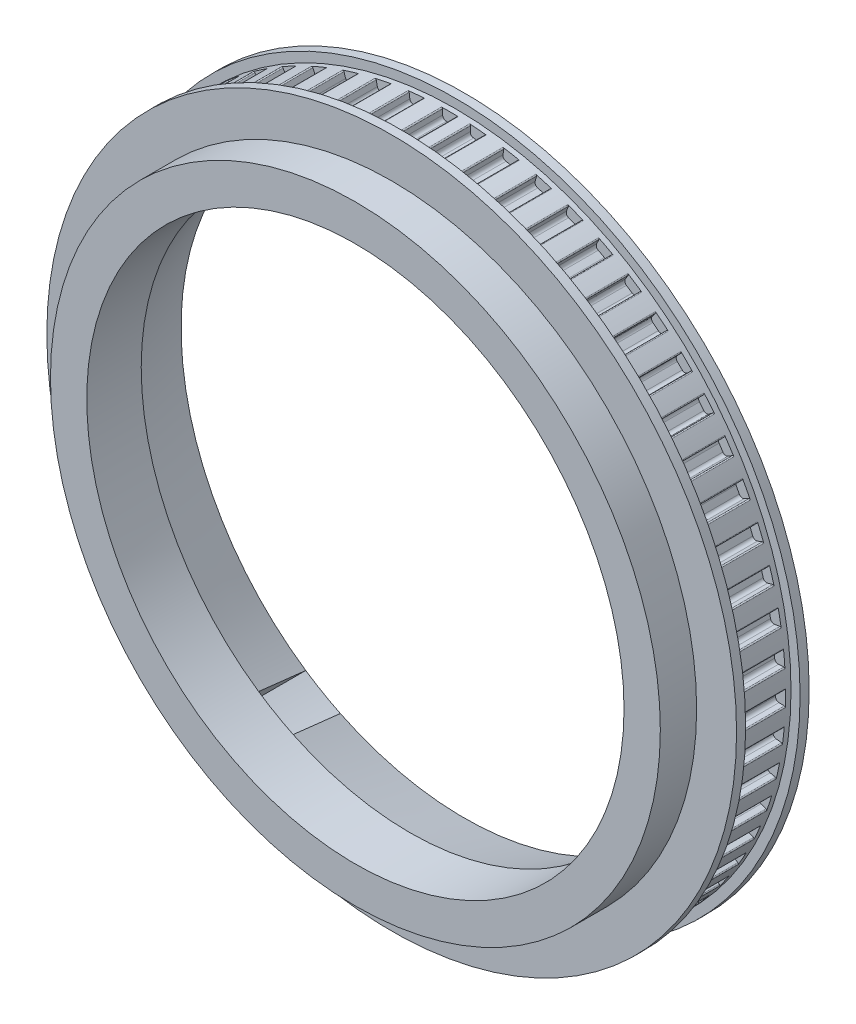
SolidWorks part; units mm, degrees
material "ABS"
ref_plane "Front Plane" through (0, 0, 0) normal (0, 0, 1) x (1, 0, 0)
ref_plane "Top Plane" through (0, 0, 0) normal (0, 1, 0) x (1, 0, 0)
ref_plane "Right Plane" through (0, 0, 0) normal (1, 0, 0) x (0, 0, -1)
sketch "Sketch2" plane through (0, 0, 0) normal (0, 1, 0) x (1, 0, 0)
  line L0 (0, -10) -> (0, 5) construction
  line L1 (37, -2.5) -> (37, -10)
  line L2 (37, -10) -> (42, -10)
  line L3 (42, -10) -> (42, -5)
  line L4 (42, -5) -> (47.5, -5)
  line L5 (47.5, -5) -> (47.5, -3.75)
  line L6 (47.5, 5) -> (39.0096, 5)
  line L7 (37, -2.5) -> (39.0096, 5)
  line L8 (47.5, 3.75) -> (46.25, 3.75)
  line L9 (46.25, 3.75) -> (46.25, -3.75)
  line L10 (46.25, -3.75) -> (47.5, -3.75)
  line L11 (47.5, 3.75) -> (47.5, 5)
  point P12 (-0.446, 0)
  point P15 (-2.0986, -0.9185)
  point P16 (0, 0)
  point P17 (46.25, 0)
  dimension "D1" = 15
  dimension "D2" = 5
  dimension "D3" = 5
  dimension "D4" = 15
  dimension "D5" = 7.5
  dimension "D6" = 47.5
  dimension "D7" = 42
  dimension "D8" = 1.25
  dimension "D9" = 7.5
revolve "Revolve1" add sketch "Sketch2" angle 360 about L0
sketch "Sketch4" plane through (0, 0, 0) normal (0, 0, -1) x (-1, 0, 0)
  line L0 (-0.9999, 46.2392) -> (-0.9701, 44.8595)
  line L1 (0.9701, 44.8595) -> (0.9999, 46.2392)
  circle A0 centre (0, 0) radius 46.25 construction
  arc A1 (-0.9999, 46.2392) -> (0.9999, 46.2392) centre (0, 0) cw
  arc A2 (-0.9701, 44.8595) -> (0.9701, 44.8595) centre (0, 0) cw
  point P8 (0, 44.87)
  point P9 (0, 46.25)
  dimension "D2" = 2
  dimension "D1" = 1.38
extrude "Cut-Extrude1" cut sketch "Sketch4" against normal mid plane 6
fillet "Fillet1" radius 0.15 2 edges at (0.9999, 46.2392, 0) (-0.9999, 46.2392, 0)
fillet "Fillet2" radius 0.5 2 edges at (-0.9701, 44.8595, 0) (0.9701, 44.8595, 0)
pattern_circular "CirPattern1" count 63 every 5.729 about axis through (0, 0, 0) along (0, 0, 1) of "Cut-Extrude1", "Fillet2", "Fillet1"
sketch "Sketch5" plane through (0, 0, -5) normal (0, 0, -1) x (-1, 0, 0)
  line L0 (-38.9126, -2.75) -> (-36.8977, -2.75)
  line L1 (-36.8977, -2.75) -> (-36.8977, 2.75)
  line L2 (-36.8977, 2.75) -> (-38.9126, 2.75)
  arc A0 (-38.9126, -2.75) -> (-38.9126, 2.75) centre (0, 0) cw
  circle A1 centre (0, 0) radius 39.0096 construction
  circle A2 centre (0, 0) radius 37 construction
  point P3 (0, 0)
  point P10 (-36.8977, 0)
  dimension "D1" = 5.5
extrude "Cut-Extrude2" cut sketch "Sketch5" against normal blind 7.5
pattern_circular "CirPattern2" count 3 over 360 about axis through (0, 0, 0) along (0, 0, 1) of "Cut-Extrude2"
